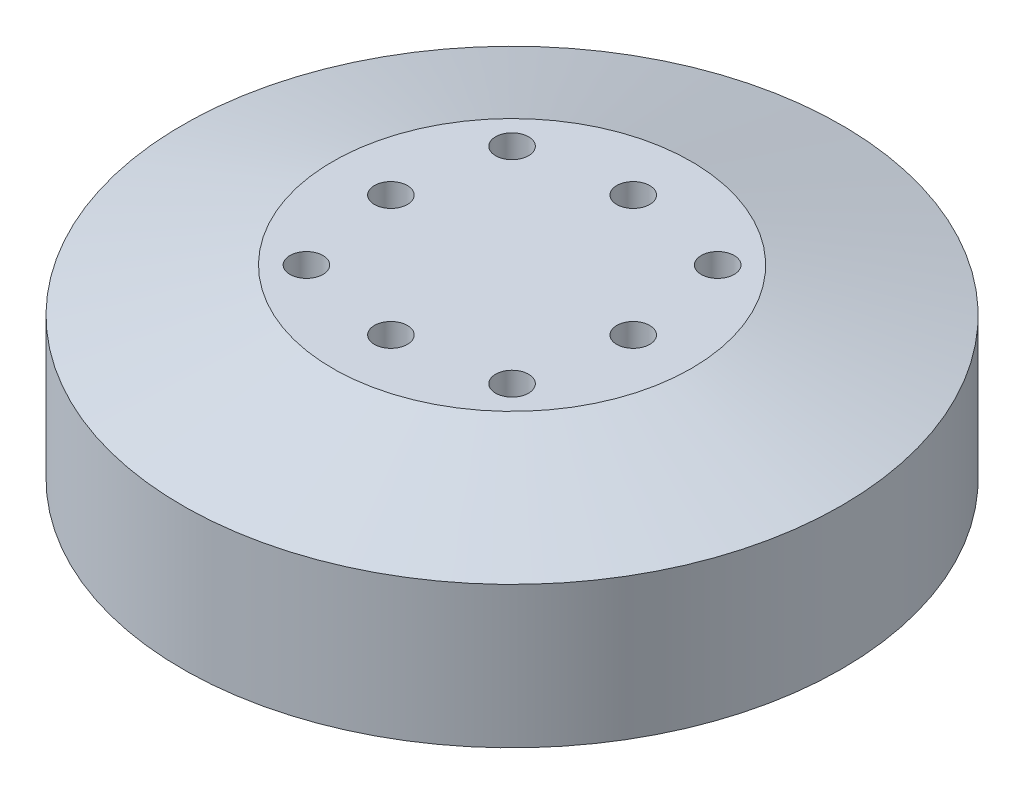
SolidWorks part; units mm, degrees
ref_plane "Front Plane" through (0, 0, 0) normal (0, 0, 1) x (1, 0, 0)
ref_plane "Top Plane" through (0, 0, 0) normal (0, 1, 0) x (1, 0, 0)
ref_plane "Right Plane" through (0, 0, 0) normal (1, 0, 0) x (0, 0, -1)
sketch "Sketch1" plane through (0, 0, 0) normal (0, 0, 1) x (1, 0, 0)
  line L0 (0, -9.55) -> (0, 9.55)
  line L1 (0, 9.55) -> (-18.5, 9.55)
  line L2 (-18.5, 9.55) -> (-34, 5.05)
  line L3 (-34, 5.05) -> (-34, -9.55)
  line L4 (-34, -9.55) -> (0, -9.55)
  point P4 (0, 0)
  dimension "D1" = 18.5
  dimension "D2" = 34
  dimension "D3" = 4.5
  dimension "D4" = 19.1
revolve "Revolve1" add sketch "Sketch1" angle 360 about L0
sketch "Sketch2" plane through (0, 9.55, 0) normal (0, 1, 0) x (1, 0, 0)
  line L0 (-10.6066, -10.6066) -> (10.6066, 10.6066) construction
  line L1 (10.6066, -10.6066) -> (-10.6066, 10.6066) construction
  line L2 (0, 0) -> (0, 12.5) construction
  circle A0 centre (0, 0) radius 12.5 construction
  circle A1 centre (0, 0) radius 15 construction
  point P3 (0, 12.5)
  point P5 (-12.5, 0)
  point P6 (0, -12.5)
  point P7 (12.5, 0)
  point P10 (0, 0)
  point P14 (0, 0)
  dimension "D1" = 25
  dimension "D2" = 30
  dimension "D3" = 45
hole_wizard "M3 Clearance Hole1" positions "Sketch3" profile "Sketch4" hole size "M3" standard "ANSI Metric"
sketch "Sketch3" plane through (0, 9.55, 0) normal (0, 1, 0) x (1, 0, 0)
  point P0 (-10.6066, 10.6066)
  point P3 (0, 12.5)
  point P6 (10.6066, 10.6066)
  point P9 (12.5, 0)
  point P12 (10.6066, -10.6066)
  point P15 (-10.6066, -10.6066)
  point P18 (-12.5, 0)
  point P21 (0, -12.5)
sketch "Sketch4" plane through (-10.6066, 9.55, -10.6066) normal (1, 0, 0) x (0, 0, 1)
  line L0 (0, 0) -> (0, 5.0215)
  line L1 (0, 5.0215) -> (1.7, 4)
  line L2 (1.7, 4) -> (1.7, 0)
  line L5 (1.7, 0) -> (0, 0)
  line L10 (0, 5.0215) -> (-1.7, 4) construction
  line L11 (0, -6.35) -> (0, 107.95) construction
  dimension "Hole Dia." = 3.4
  dimension "Hole Depth" = 4
  dimension "Drill Angle" = 118
sketch "Sketch5" plane through (0, -9.55, 0) normal (0, -1, 0) x (1, 0, 0)
  circle A4 centre (0, 0) radius 32
  circle A5 centre (0, 0) radius 32
  dimension "D1" = 2
extrude "Cut-Extrude1" cut sketch "Sketch5" against normal blind 1
